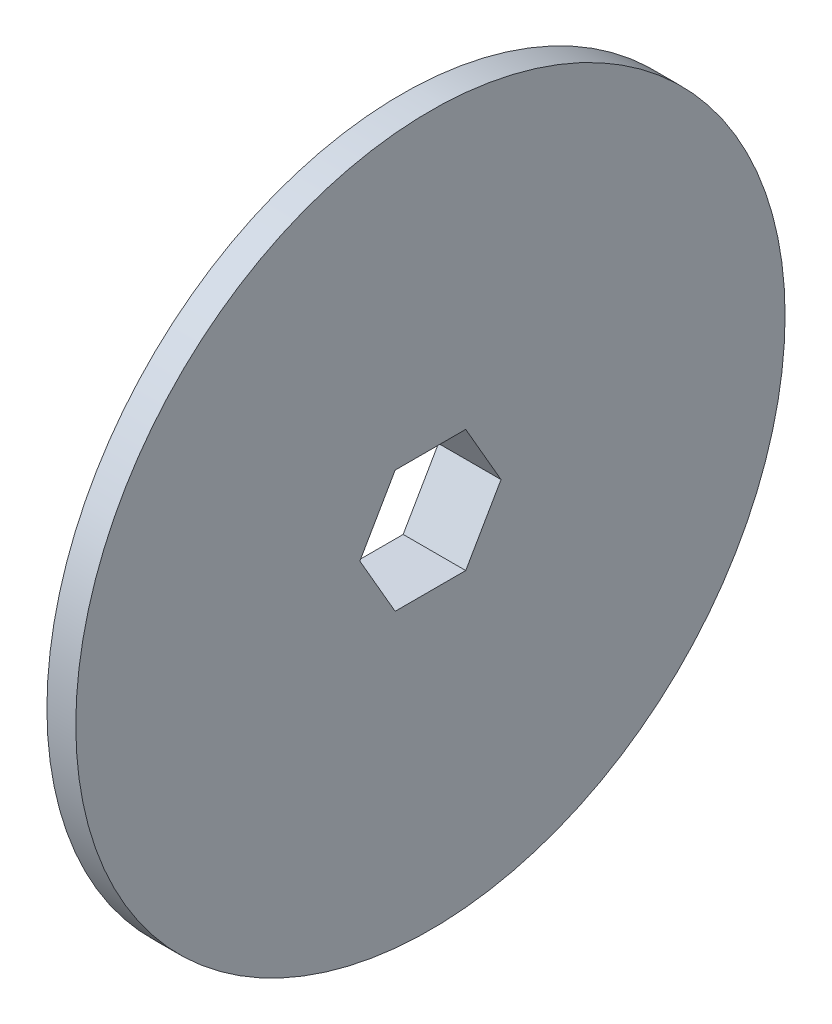
SolidWorks part; units mm, degrees
ref_plane "Alzado" through (0, 0, 0) normal (0, 0, 1) x (1, 0, 0)
ref_plane "Planta" through (0, 0, 0) normal (0, 1, 0) x (1, 0, 0)
ref_plane "Vista lateral" through (0, 0, 0) normal (1, 0, 0) x (0, 0, -1)
sketch "Croquis1" plane through (0, 0, 0) normal (1, 0, 0) x (0, 0, -1)
  line L1 (7.3323, 0) -> (3.6662, 6.35)
  line L2 (3.6662, 6.35) -> (-3.6662, 6.35)
  line L3 (-3.6662, 6.35) -> (-7.3323, 0)
  line L4 (-7.3323, 0) -> (-3.6662, -6.35)
  line L5 (-3.6662, -6.35) -> (3.6662, -6.35)
  line L6 (3.6662, -6.35) -> (7.3323, 0)
  circle A0 centre (0, 0) radius 14.345
  circle A1 centre (0, 0) radius 6.35 construction
  dimension "D1" = 28.69
  dimension "D2" = 12.7
extrude "Saliente-Extruir1" add sketch "Croquis1" along normal blind 3.5
sketch "Croquis2" plane through (3.5, 0, 0) normal (1, 0, 0) x (0, 0, -1)
  line L1 (7.3323, 0) -> (3.6662, 6.35)
  line L2 (3.6662, 6.35) -> (-3.6662, 6.35)
  line L3 (-3.6662, 6.35) -> (-7.3323, 0)
  line L4 (-7.3323, 0) -> (-3.6662, -6.35)
  line L5 (-3.6662, -6.35) -> (3.6662, -6.35)
  line L6 (3.6662, -6.35) -> (7.3323, 0)
  circle A0 centre (0, 0) radius 36.845
  circle A1 centre (0, 0) radius 6.35 construction
  dimension "D1" = 73.69
extrude "Saliente-Extruir2" add sketch "Croquis2" along normal blind 3
